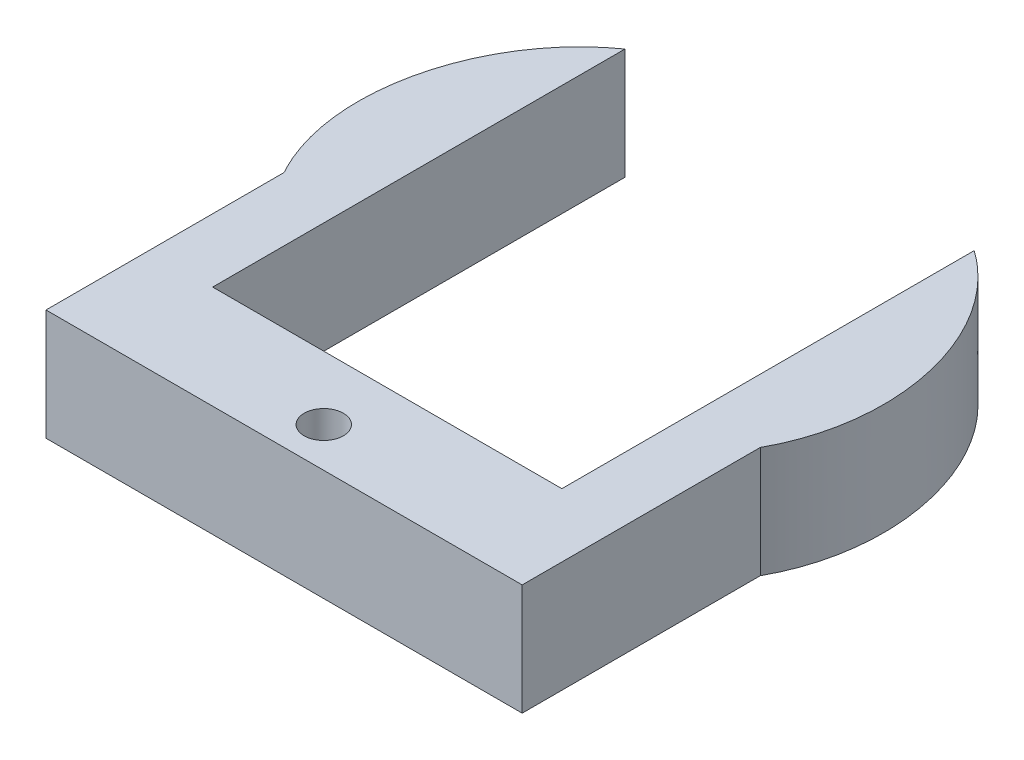
SolidWorks part; units mm, degrees
ref_plane "Front Plane" through (0, 0, 0) normal (0, 0, 1) x (1, 0, 0)
ref_plane "Top Plane" through (0, 0, 0) normal (0, 1, 0) x (1, 0, 0)
ref_plane "Right Plane" through (0, 0, 0) normal (1, 0, 0) x (0, 0, -1)
sketch "Sketch1" plane through (0, 0, 0) normal (0, 1, 0) x (1, 0, 0)
  line L0 (8, 67.5015) -> (8, 79.9541)
  line L3 (8, 28) -> (52, 28)
  line L8 (8, 28) -> (8, 67.5015)
  line L12 (52, 28) -> (52, 70.2973)
  line L13 (30, 28) -> (30, 82.123) construction
  line L14 (52, 70.2973) -> (52, 79.9541)
  line L16 (0, 45) -> (0, 15)
  line L17 (0, 15) -> (60, 15)
  line L18 (60, 15) -> (60, 45)
  arc A0 (11.5, 82) -> (0, 45) centre (24.25, 57.75) ccw construction
  spline S0 degree 3 poles (0, 45) (-4.2674, 52.7022) (-3.8497, 67.2321) (4.5722, 77.5249) (8, 79.9541) knots 0 0 0 0 0.616859 0.907352 0.907352 0.907352 0.907352
  spline S1 degree 3 poles (60, 45) (64.2674, 52.7022) (63.8497, 67.2321) (55.4278, 77.5249) (52, 79.9541) knots 0 0 0 0 0.616859 0.907352 0.907352 0.907352 0.907352
extrude "Boss-Extrude1" add sketch "Sketch1" along normal blind 14
sketch "Sketch3" plane through (0, 0, 0) normal (0, -1, 0) x (1, 0, 0)
  circle A0 centre (30, -20) radius 2.4697
extrude "Cut-Extrude1" cut sketch "Sketch3" against normal blind 21
